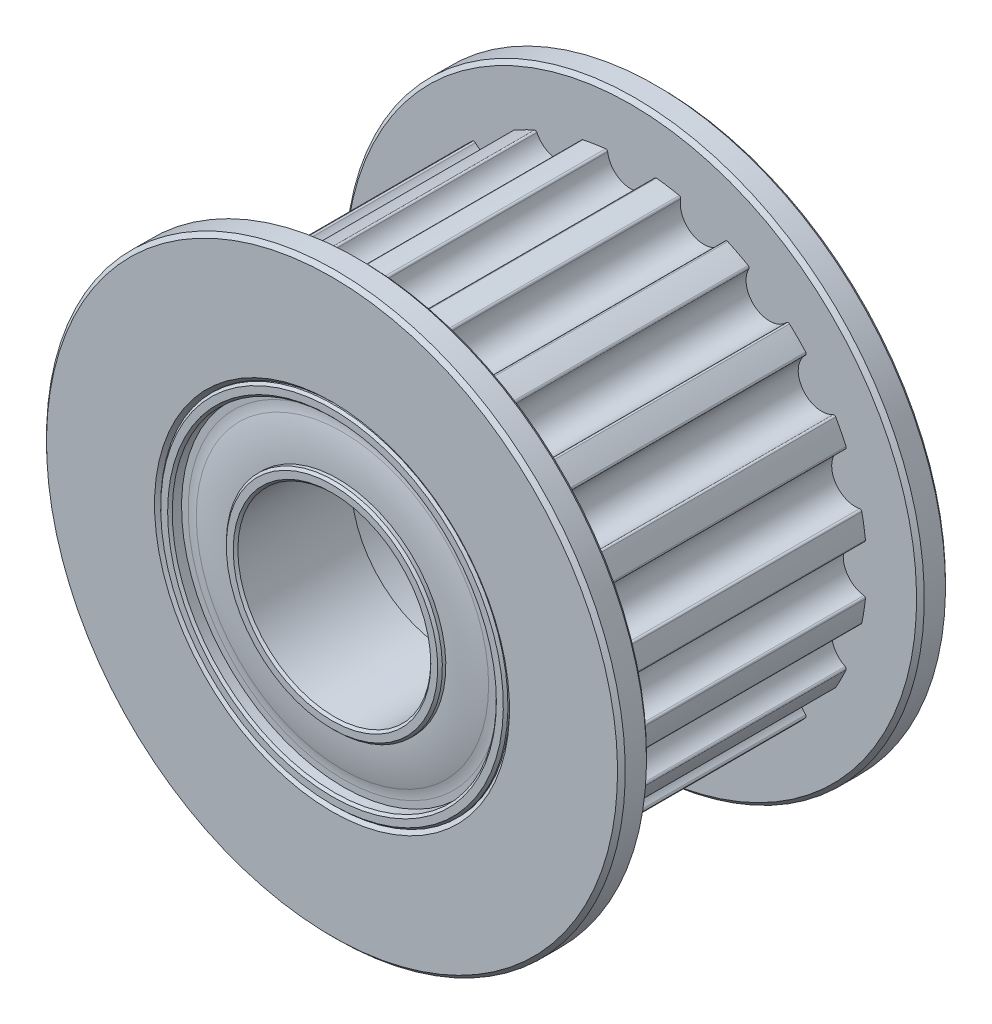
SolidWorks part; units mm, degrees
ref_plane "Front" through (0, 0, 0) normal (0, 0, 1) x (1, 0, 0)
ref_plane "Top" through (0, 0, 0) normal (0, 1, 0) x (1, 0, 0)
ref_plane "Right" through (0, 0, 0) normal (1, 0, 0) x (0, 0, -1)
sketch "Sketch1" plane through (0, 0, 0) normal (1, 0, 0) x (0, 0, -1)
  line L0 (-4.25, 0) -> (4.25, 0) construction
  line L1 (4.25, 7.5) -> (4.25, -7.5) construction
  line L2 (4.25, 7.5) -> (3.5, 7.5) construction
  line L3 (4.25, 2.5) -> (4.25, -2.5) construction
  line L4 (4.25, 6.11) -> (4.25, -6.11) construction
  line L5 (3, 0) -> (-3, 0) construction
  line L6 (3.5, 7.5) -> (3.5, 6.11) construction
  line L7 (4.25, 4.5) -> (1.25, 4.5) construction
  line L8 (1.25, 4.5) -> (1.25, 2.5) construction
  line L9 (1.25, 2.5) -> (4.25, 2.5) construction
  line L10 (4.25, 4.5) -> (4.25, -4.5) construction
  line L11 (-4.25, 0) -> (-4.25, 7.5) construction
  line L12 (-4.25, 7.5) -> (-3.5, 7.5) construction
  line L13 (-3.5, 7.5) -> (-3.5, 6.11) construction
  line L14 (-3.5, 6.11) -> (3.5, 6.11) construction
  line L15 (3.5, 6.11) -> (3.5, -6.11) construction
  line L16 (3.5, -6.11) -> (-3.5, -6.11) construction
  line L17 (-3.5, -6.11) -> (-3.5, 6.11) construction
  line L18 (0, -3.5) -> (0, 3.5) construction
  point P15 (4.25, 0)
  point P22 (3.5, 0)
  point P24 (-3, -6.11)
  point P25 (3, -6.11)
  point P29 (0, 0)
  dimension "Width" = 8.5
  dimension "OD" = 15
  dimension "ID" = 5
  dimension "Diameter" = 12.22
  dimension "Groove Depth" = 1.39
  dimension "For Maximum Belt Width" = 6
  dimension "For Shaft Diameter" = 5
  dimension "Bearing Diameter" = 9
  dimension "Bearing Width" = 3
  dimension "Inside Width" = 7
  dimension "Wall Thickness" = 0.75
  dimension "D1" = 7
sketch "Sketch5" plane through (0, 0, 0) normal (0, 0, 1) x (1, 0, 0)
  circle A0 centre (0, 0) radius 7.5 construction
  circle A1 centre (0, 0) radius 6.11 construction
  circle A2 centre (0, 0) radius 2.5 construction
  point P5 (0, 0)
  point P9 (-6.11, 0)
  point P10 (-7.5, 0)
  point P13 (0, 6.11)
sketch "Sketch2" plane through (0, 0, 0) normal (1, 0, 0) x (0, 0, -1)
  line L0 (4.25, 2.5) -> (1.25, 2.5)
  line L1 (4.25, 2.5) -> (4.25, 2.8)
  line L2 (4.25, 7.5) -> (4.25, -7.5) construction
  line L3 (4.25, 2.8) -> (3.95, 2.8) construction
  line L4 (4.1, 4.2) -> (4.1, 2.8) construction
  line L5 (4.25, 4.5) -> (1.25, 4.5)
  line L6 (3.95, 3.9) -> (3.95, 4.2)
  line L7 (4.25, 4.5) -> (4.25, 4.2)
  line L8 (4.25, 4.2) -> (3.95, 4.2)
  line L9 (3.95, 4.2) -> (3.95, 2.8) construction
  line L10 (1.25, 4.5) -> (1.25, 2.5)
  line L11 (4.1, 2.8) -> (4.25, 2.8)
  arc A0 (3.95, 3.9) -> (4.1, 2.8) centre (-0.0083, 2.8) cw
  dimension "D1" = 0.3
revolve "Revolve1" add sketch "Sketch2" angle 360 about L0
chamfer "Chamfer2" distance 0.06 angle 45 4 edges at (0, -2.8, -4.25) (0, -2.5, -4.25) (0, -4.2, -4.25) (0, -4.5, -4.25)
fillet "Fillet2" radius 1 1 edges at (0, -3.9, -3.95)
mirror "Mirror1" about plane through (0, 0, 0) normal (0, 0, 1) of bodies 108
sketch "Sketch3" plane through (0, 0, 0) normal (1, 0, 0) x (0, 0, -1)
  line L0 (3.5, 7.5) -> (4.25, 7.5)
  line L1 (4.25, 7.5) -> (4.25, 4.5)
  line L2 (4.25, 7.5) -> (4.25, -7.5) construction
  line L3 (-4.25, 4.5) -> (-1.25, 4.5)
  line L4 (-1.25, 4.5) -> (-1.25, 3.5)
  line L5 (-1.25, 3.5) -> (1.25, 3.5)
  line L6 (1.25, 3.5) -> (1.25, 4.5)
  line L8 (1.25, 4.5) -> (4.25, 4.5)
  line L9 (3.5, 7.5) -> (3.5, 6.11)
  line L10 (3.5, 6.11) -> (-3.5, 6.11)
  line L11 (0, 6.11) -> (0, 4.5) construction
  line L12 (-4.25, 4.5) -> (4.25, 4.5) construction
  line L13 (-3.5, 7.5) -> (-3.5, 6.11)
  line L19 (-4.25, 7.5) -> (-4.25, 4.5)
  line L20 (-3.5, 7.5) -> (-4.25, 7.5)
revolve "Revolve2" add sketch "Sketch3" angle 360 about L0
chamfer "Chamfer1" distance 0.1 angle 45 6 edges at (0, -7.5, -4.25) (0, -7.5, -3.5) (0, -7.5, 3.5) (0, -7.5, 4.25) (0, -4.5, -4.25) (0, -4.5, 4.25)
sketch "Sketch4" plane through (0, 0, 0) normal (0, 0, 1) x (1, 0, 0)
  line L0 (-0.611, 6.11) -> (0.611, 6.11)
  line L1 (-0.611, 6.11) -> (-0.611, 5.554) construction
  line L2 (-0.611, 5.554) -> (0.611, 5.554) construction
  line L3 (0.611, 5.554) -> (0.611, 6.11) construction
  line L4 (0, 6.11) -> (0, 5.554) construction
  arc A0 (0.611, 6.11) -> (-0.611, 6.11) centre (0, 6.11) cw
  dimension "D1" = 0.556
  dimension "D3" = 1.222
extrude "Cut-Extrude1" cut sketch "Sketch4" against normal up to surface and the other way up to surface
fillet "Fillet1" radius 0.05 2 edges at (-0.6102, 6.0795, 0) (0.6102, 6.0795, 0)
pattern_circular "CirPattern3" count 20 over 360 about axis through (0, 0, 0) along (0, 0, 1) of "Cut-Extrude1", "Fillet1"
equation "\"D1@Sketch4\"=\"Groove Depth@Sketch1\"/2.5"
equation "\"D3@Sketch4\"=\"Diameter@Sketch1\"/10"
equation "\"D1@Sketch1\"=\"ID@Sketch1\"+2"
